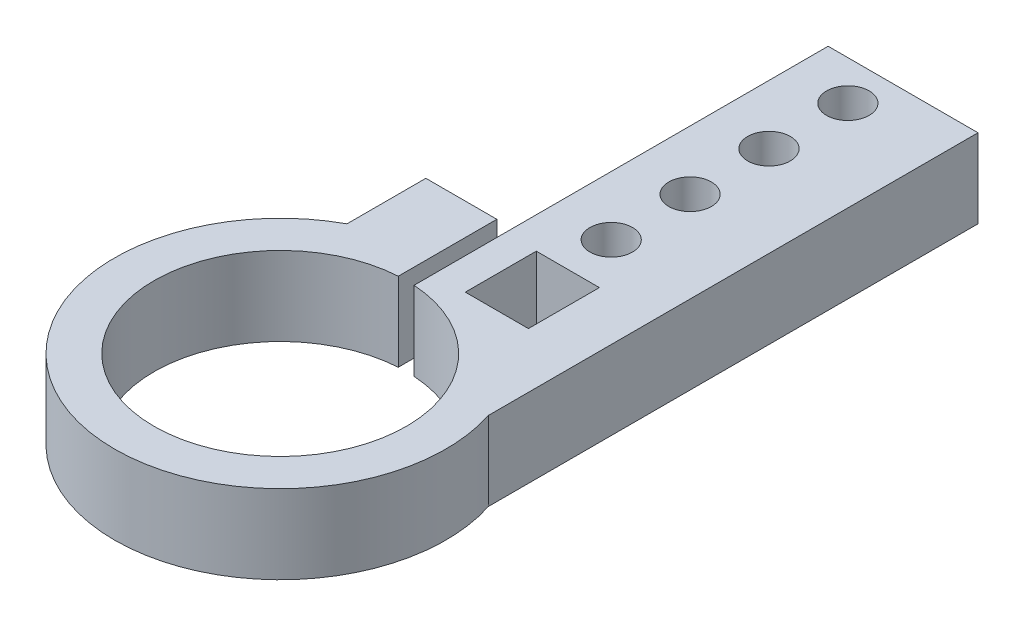
SolidWorks part; units mm, degrees
ref_plane "Front Plane" through (0, 0, 0) normal (0, 0, 1) x (1, 0, 0)
ref_plane "Top Plane" through (0, 0, 0) normal (0, 1, 0) x (1, 0, 0)
ref_plane "Right Plane" through (0, 0, 0) normal (1, 0, 0) x (0, 0, -1)
sketch "Sketch1" plane through (0, 0, 0) normal (0, 1, 0) x (1, 0, 0)
  circle A0 centre (0, 0) radius 20.32
  circle A1 centre (0, 0) radius 26.67
  dimension "D1" = 40.64
  dimension "D2" = 53.34
extrude "Boss-Extrude1" add sketch "Sketch1" along normal blind 12.7
sketch "Sketch2" plane through (0, 0, 0) normal (0, 1, 0) x (1, 0, 0)
  line L1 (12.7, 36.1521) -> (-12.7, 36.1521)
  line L2 (12.7, 36.1521) -> (12.7, 23.4521)
  line L3 (12.7, 23.4521) -> (-12.7, 23.4521)
  line L4 (-12.7, 36.1521) -> (-12.7, 23.4521)
  line L5 (12.7, 36.1521) -> (-12.7, 23.4521) construction
  line L6 (12.7, 23.4521) -> (-12.7, 36.1521) construction
  circle A0 centre (0, 0) radius 26.67 construction
  point P0 (0, 29.8021)
  dimension "D1" = 25.4
  dimension "D2" = 12.7
extrude "Boss-Extrude2" add sketch "Sketch2" along normal blind 12.7
sketch "Sketch4" plane through (0, 0, 0) normal (0, 1, 0) x (1, 0, 0)
  line L1 (-1.27, 1.4316) -> (1.27, 1.4316)
  line L2 (-1.27, 1.4316) -> (-1.27, 60.42)
  line L3 (-1.27, 60.42) -> (1.27, 60.42)
  line L4 (1.27, 1.4316) -> (1.27, 60.42)
  line L5 (-1.27, 1.4316) -> (1.27, 60.42) construction
  line L6 (-1.27, 60.42) -> (1.27, 1.4316) construction
  point P0 (0, 30.9258)
  dimension "D1" = 2.54
extrude "Cut-Extrude2" cut sketch "Sketch4" along normal through all
sketch "Sketch5" plane through (12.7, 0, 0) normal (1, 0, 0) x (0, 0, -1)
  line L1 (36.1521, 12.7) -> (0, 12.7)
  line L2 (36.1521, 12.7) -> (36.1521, 0)
  line L3 (36.1521, 0) -> (0, 0)
  line L4 (0, 12.7) -> (0, 0)
extrude "Boss-Extrude3" add sketch "Sketch5" against normal up to next from offset 12.7
sketch "Sketch6" plane through (0, 12.7, 0) normal (0, 1, 0) x (1, 0, 0)
  line L0 (1.27, 20.2803) -> (1.27, 36.1521) construction
  line L1 (25.4, 36.1521) -> (1.27, 36.1521)
  line L2 (25.4, 36.1521) -> (25.4, 86.9521)
  line L3 (25.4, 86.9521) -> (1.27, 86.9521)
  line L4 (1.27, 36.1521) -> (1.27, 86.9521)
  dimension "D1" = 50.8
extrude "Boss-Extrude4" add sketch "Sketch6" against normal blind 12.7
sketch "Sketch7" plane through (0, 0, 0) normal (0, 1, 0) x (1, 0, 0)
  line L0 (25.4, 86.9521) -> (1.27, 86.9521) construction
  line L2 (1.27, 20.2803) -> (1.27, 86.9521) construction
  line L4 (6.35, 34.8821) -> (16.51, 34.8821)
  line L5 (6.35, 34.8821) -> (6.35, 23.4521)
  line L6 (6.35, 23.4521) -> (16.51, 23.4521)
  line L7 (16.51, 34.8821) -> (16.51, 23.4521)
  circle A0 centre (10.795, 80.6021) radius 3.429
  circle A1 centre (36.195, 80.6021) radius 3.429
  circle A2 centre (36.195, 67.9021) radius 3.429
  circle A3 centre (10.795, 67.9021) radius 3.429
  circle A4 centre (10.795, 55.2021) radius 3.429
  circle A5 centre (36.195, 55.2021) radius 3.429
  circle A6 centre (10.795, 42.5021) radius 3.429
  circle A7 centre (36.195, 42.5021) radius 3.429
  dimension "D1" = 6.858
  dimension "D9" = 12.7
  dimension "D2" = 6.35
  dimension "D3" = 9.525
  dimension "D6" = 11.43
  dimension "D7" = 5.08
  dimension "D8" = 10.16
  dimension "D4" = 2
  dimension "D5" = 4
extrude "Cut-Extrude3" cut sketch "Sketch7" along normal through all
